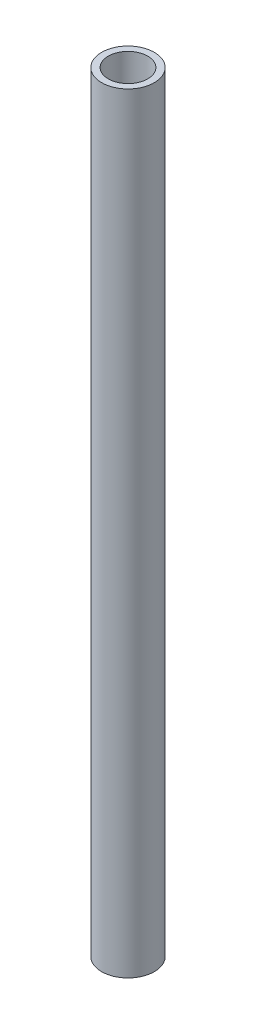
SolidWorks part; units mm, degrees
material "Thornel Mat VMA"
ref_plane "前视基准面" through (0, 0, 0) normal (0, 0, 1) x (1, 0, 0)
ref_plane "上视基准面" through (0, 0, 0) normal (0, 1, 0) x (1, 0, 0)
ref_plane "右视基准面" through (0, 0, 0) normal (1, 0, 0) x (0, 0, -1)
other "Configuration Table"
sketch "草图1" plane through (0, 0, 0) normal (0, 1, 0) x (1, 0, 0)
  circle A0 centre (0, 0) radius 4
  circle A1 centre (0, 0) radius 3
extrude "凸台-拉伸1" add sketch "草图1" along normal blind 117
